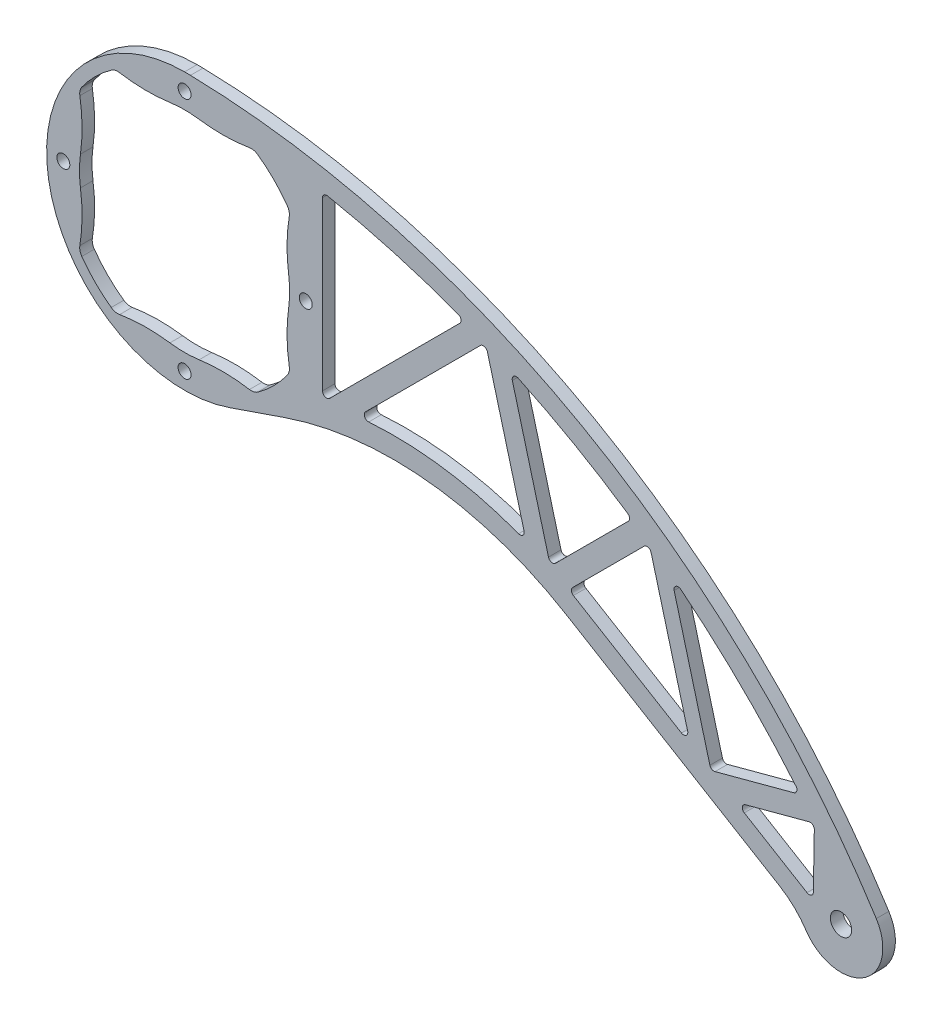
SolidWorks part; units mm, degrees
material "6061 合金"
ref_plane "前视基准面" through (0, 0, 0) normal (0, 0, 1) x (1, 0, 0)
ref_plane "上视基准面" through (0, 0, 0) normal (0, 1, 0) x (1, 0, 0)
ref_plane "右视基准面" through (0, 0, 0) normal (1, 0, 0) x (0, 0, -1)
other "Configuration Table"
sketch "草图2" plane through (0, 0, 0) normal (0, 0, 1) x (1, 0, 0)
  line L1 (10.7304, -31.2067) -> (23.987, -26.6485)
  line L2 (91.2325, -33.7454) -> (142.3676, -64.5004)
  line L3 (0, 0) -> (154.4016, 0) construction
  line L4 (0, 0) -> (157.0595, -65.0562) construction
  line L5 (0, 0) -> (0, -130.9869) construction
  arc A24 (0, 33) -> (10.7304, -31.2067) centre (0, 0) ccw
  arc A25 (148.7262, -70.5839) -> (165.4995, -59.6928) centre (157.0595, -65.0562) ccw
  arc A26 (1.4146, 32.9833) -> (165.4995, -59.6928) centre (-3.3007, -166.9611) cw
  circle A27 centre (-29, 0) radius 1.55
  arc A28 (23.987, -26.6485) -> (91.2325, -33.7454) centre (50, -102.3011) cw
  arc A29 (142.3676, -64.5004) -> (148.7262, -70.5839) centre (132.0595, -81.6393) cw
  arc A30 (1.4146, 32.9833) -> (0, 33) centre (0, -27) ccw
  arc A32 (-24.8547, -15.5614) -> (-24.7074, -3.4705) centre (-64.3186, -9.0345) ccw construction
  arc A33 (-24.8547, -15.5614) -> (-24.4235, -17.4211) centre (-22.3882, -15.9693) ccw construction
  arc A34 (-24.4235, -17.4211) -> (-17.4211, -24.4235) centre (0, 0) ccw construction
  arc A35 (-17.4211, -24.4235) -> (-15.5614, -24.8547) centre (-15.9693, -22.3882) ccw construction
  arc A36 (-3.4705, -24.7074) -> (-15.5614, -24.8547) centre (-9.0345, -64.3186) ccw construction
  arc A37 (-3.4705, -24.7074) -> (3.4705, -24.7074) centre (0, 0) ccw construction
  arc A38 (15.5614, -24.8547) -> (3.4705, -24.7074) centre (9.0345, -64.3186) ccw construction
  arc A39 (15.5614, -24.8547) -> (17.4211, -24.4235) centre (15.9693, -22.3882) ccw construction
  arc A40 (17.4211, -24.4235) -> (24.4235, -17.4211) centre (0, 0) ccw construction
  arc A41 (24.4235, -17.4211) -> (24.8547, -15.5614) centre (22.3882, -15.9693) ccw construction
  arc A42 (24.7074, -3.4705) -> (24.8547, -15.5614) centre (64.3186, -9.0345) ccw construction
  arc A43 (24.7074, -3.4705) -> (24.7074, 3.4705) centre (0, 0) ccw construction
  arc A44 (24.8547, 15.5614) -> (24.7074, 3.4705) centre (64.3186, 9.0345) ccw construction
  arc A45 (24.8547, 15.5614) -> (24.4235, 17.4211) centre (22.3882, 15.9693) ccw construction
  arc A46 (24.4235, 17.4211) -> (17.4211, 24.4235) centre (0, 0) ccw construction
  arc A47 (17.4211, 24.4235) -> (15.5614, 24.8547) centre (15.9693, 22.3882) ccw construction
  arc A48 (3.4705, 24.7074) -> (15.5614, 24.8547) centre (9.0345, 64.3186) ccw construction
  arc A49 (3.4705, 24.7074) -> (-3.4705, 24.7074) centre (0, 0) ccw construction
  arc A50 (-15.5614, 24.8547) -> (-3.4705, 24.7074) centre (-9.0345, 64.3186) ccw construction
  arc A51 (-15.5614, 24.8547) -> (-17.4211, 24.4235) centre (-15.9693, 22.3882) ccw construction
  arc A52 (-17.4211, 24.4235) -> (-24.4235, 17.4211) centre (0, 0) ccw construction
  arc A53 (-24.4235, 17.4211) -> (-24.8547, 15.5614) centre (-22.3882, 15.9693) ccw construction
  arc A54 (-24.7074, 3.4705) -> (-24.8547, 15.5614) centre (-64.3186, 9.0345) ccw construction
  arc A55 (-24.7074, 3.4705) -> (-24.7074, -3.4705) centre (0, 0) ccw construction
  arc A56 (-17.4792, 24.5049) -> (-24.5049, 17.4792) centre (0, 0) ccw
  arc A57 (-24.5049, 17.4792) -> (-24.9533, 15.5451) centre (-22.3882, 15.9693) ccw
  arc A58 (-24.8065, 3.4845) -> (-24.9533, 15.5451) centre (-64.3186, 9.0345) ccw
  arc A59 (-24.8065, 3.4845) -> (-24.8065, -3.4845) centre (0, 0) ccw
  arc A60 (-24.9533, -15.5451) -> (-24.8065, -3.4845) centre (-64.3186, -9.0345) ccw
  arc A61 (-24.9533, -15.5451) -> (-24.5049, -17.4792) centre (-22.3882, -15.9693) ccw
  arc A62 (-24.5049, -17.4792) -> (-17.4792, -24.5049) centre (0, 0) ccw
  arc A63 (-17.4792, -24.5049) -> (-15.5451, -24.9533) centre (-15.9693, -22.3882) ccw
  arc A64 (-3.4845, -24.8065) -> (-15.5451, -24.9533) centre (-9.0345, -64.3186) ccw
  arc A65 (-3.4845, -24.8065) -> (3.4845, -24.8065) centre (0, 0) ccw
  arc A66 (15.5451, -24.9533) -> (3.4845, -24.8065) centre (9.0345, -64.3186) ccw
  arc A67 (15.5451, -24.9533) -> (17.4792, -24.5049) centre (15.9693, -22.3882) ccw
  arc A68 (17.4792, -24.5049) -> (24.5049, -17.4792) centre (0, 0) ccw
  arc A69 (24.5049, -17.4792) -> (24.9533, -15.5451) centre (22.3882, -15.9693) ccw
  arc A70 (24.8065, -3.4845) -> (24.9533, -15.5451) centre (64.3186, -9.0345) ccw
  arc A71 (24.8065, -3.4845) -> (24.8065, 3.4845) centre (0, 0) ccw
  arc A72 (24.9533, 15.5451) -> (24.8065, 3.4845) centre (64.3186, 9.0345) ccw
  arc A73 (24.9533, 15.5451) -> (24.5049, 17.4792) centre (22.3882, 15.9693) ccw
  arc A74 (24.5049, 17.4792) -> (17.4792, 24.5049) centre (0, 0) ccw
  arc A75 (17.4792, 24.5049) -> (15.5451, 24.9533) centre (15.9693, 22.3882) ccw
  arc A76 (3.4845, 24.8065) -> (15.5451, 24.9533) centre (9.0345, 64.3186) ccw
  arc A77 (3.4845, 24.8065) -> (-3.4845, 24.8065) centre (0, 0) ccw
  arc A78 (-15.5451, 24.9533) -> (-3.4845, 24.8065) centre (-9.0345, 64.3186) ccw
  arc A79 (-15.5451, 24.9533) -> (-17.4792, 24.5049) centre (-15.9693, 22.3882) ccw
  circle A80 centre (0, 0) radius 29 construction
  circle A81 centre (0, 29) radius 1.55
  circle A82 centre (0, -29) radius 1.55
  arc A83 (15.5614, -24.8547) -> (3.4705, -24.7074) centre (9.0345, -64.3186) ccw construction
  circle A84 centre (29, 0) radius 1.55
  point P51 (147.0595, -65.0562)
  point P60 (29, 0)
  dimension "D3" = 3.1
  dimension "D5" = 66
  dimension "D6" = 20
  dimension "D7" = 80
  dimension "D9" = 20
  dimension "D10" = 200
  dimension "D11" = 60
  dimension "D13" = 50
  dimension "D1" = 170
  dimension "D2" = 130
  dimension "D4" = 29
  dimension "D8" = 22.5
  dimension "D12" = 0.1
  dimension "D14" = 25
extrude "凸台-拉伸1" add sketch "草图2" along normal blind 3
sketch "草图7" plane through (0, 0, 3) normal (0, 0, 1) x (1, 0, 0)
  circle A0 centre (157.0595, -65.0562) radius 2.55
  arc A1 (148.7262, -70.5839) -> (165.4995, -59.6928) centre (157.0595, -65.0562) ccw construction
  dimension "D1" = 5.1
extrude "切除-拉伸2" cut sketch "草图7" against normal blind 5
sketch "草图9" plane through (0, 0, 3) normal (0, 0, 1) x (1, 0, 0)
  line L0 (93.8095, -29.4607) -> (77.7146, -19.7805) construction
  line L2 (10.7304, -31.2067) -> (23.987, -26.6485)
  line L3 (91.2325, -33.7454) -> (142.3676, -64.5004)
  line L6 (33, 23.4192) -> (33, -16.6042)
  line L7 (34.7071, -17.3113) -> (65.8687, 13.8502)
  line L8 (70.7773, 11.6878) -> (43.2854, -15.8041)
  line L9 (72.4503, 11.2395) -> (81.2349, -21.5452)
  line L10 (78.4208, 8.276) -> (87.0701, -24.0039)
  line L11 (88.7431, -24.4522) -> (106.1707, -7.0247)
  line L12 (14.8183, -31.2257) -> (-22.149, -67.7394) construction
  line L13 (-23.9266, -76.5229) -> (-33.3984, -85.8785) construction
  line L14 (109.9456, -10.3208) -> (92.8385, -27.4279)
  line L15 (93.0302, -28.992) -> (118.8884, -44.5443)
  line L16 (93.8095, -29.4607) -> (144.9447, -60.2157) construction
  line L17 (91.2325, -33.7454) -> (142.3676, -64.5004) construction
  line L18 (111.6187, -10.7691) -> (120.3697, -43.4285)
  line L29 (117.1346, -15.8999) -> (125.6886, -47.8239)
  line L30 (93.8095, -29.4607) -> (144.9447, -60.2157)
  line L31 (93.8095, -29.4607) -> (144.9447, -60.2157) construction
  line L32 (126.9133, -48.531) -> (145.7798, -43.4758)
  line L33 (149.4125, -47.6788) -> (134.1757, -51.7615)
  line L34 (150.6712, -48.6626) -> (150.4368, -61.7685)
  line L35 (133.9191, -53.5844) -> (148.9215, -62.6075)
  arc A1 (79.917, -22.74) -> (44.0624, -17.5087) centre (50, -102.3011) ccw
  arc A7 (148.7262, -70.5839) -> (142.3676, -64.5004) centre (132.0595, -81.6393) ccw
  arc A8 (148.7262, -70.5839) -> (165.4995, -59.6928) centre (157.0595, -65.0562) ccw
  arc A9 (165.4995, -59.6928) -> (1.4146, 32.9833) centre (-3.3007, -166.9611) ccw
  arc A10 (1.4146, 32.9833) -> (0, 33) centre (0, -27) ccw
  arc A11 (117.1346, -15.8999) -> (118.7263, -14.861) centre (118.1005, -15.641) cw
  arc A12 (0, 33) -> (10.7304, -31.2067) centre (0, 0) ccw
  arc A13 (91.2325, -33.7454) -> (23.987, -26.6485) centre (50, -102.3011) ccw
  arc A15 (148.7262, -70.5839) -> (156.4086, -55.0774) centre (157.0595, -65.0562) ccw construction
  arc A21 (161.2795, -62.3745) -> (1.2967, 27.9847) centre (-3.3007, -166.9611) ccw construction
  arc A22 (93.8095, -29.4607) -> (-33.3984, -85.8785) centre (50, -102.3011) ccw construction
  arc A23 (65.5144, 15.493) -> (34.1923, 24.4006) centre (-3.3007, -166.9611) ccw
  arc A24 (106.0242, -5.4895) -> (79.8129, 9.4394) centre (-3.3007, -166.9611) ccw
  arc A27 (152.8929, -67.82) -> (144.9447, -60.2157) centre (132.0595, -81.6393) ccw construction
  arc A28 (165.4995, -59.6928) -> (1.4146, 32.9833) centre (-3.3007, -166.9611) ccw construction
  arc A29 (1.2967, 27.9847) -> (-23.9266, -76.5229) centre (0, -27) ccw construction
  arc A30 (1.4146, 32.9833) -> (15.1955, 31.0439) centre (0, -27) ccw construction
  circle A31 centre (3.5031, 49.1035) radius 21.5142 construction
  arc A32 (-23.9266, -76.5229) -> (-23.9266, -76.5229) centre (-23.9266, -76.5229) ccw construction
  arc A33 (-23.9266, -76.5229) -> (-23.9266, -76.5229) centre (-23.9266, -76.5229) cw construction
  arc A34 (15.1955, 31.0439) -> (14.8183, -31.2257) centre (0, 0) ccw construction
  arc A35 (91.2325, -33.7454) -> (-22.149, -67.7394) centre (50, -102.3011) ccw construction
  arc A36 (148.7262, -70.5839) -> (142.3676, -64.5004) centre (132.0595, -81.6393) ccw construction
  arc A37 (148.7262, -70.5839) -> (165.4995, -59.6928) centre (157.0595, -65.0562) ccw construction
  arc A38 (152.8929, -67.82) -> (161.2795, -62.3745) centre (157.0595, -65.0562) ccw construction
  arc A42 (92.8385, -27.4279) -> (93.0302, -28.992) centre (93.5456, -28.135) ccw
  arc A43 (109.9456, -10.3208) -> (111.6187, -10.7691) centre (110.6527, -11.0279) cw
  arc A44 (106.1707, -7.0247) -> (106.0242, -5.4895) centre (105.4636, -6.3176) ccw
  arc A45 (78.4208, 8.276) -> (79.8129, 9.4394) centre (79.3867, 8.5348) cw
  arc A46 (87.0701, -24.0039) -> (88.7431, -24.4522) centre (88.036, -23.7451) ccw
  arc A47 (43.2854, -15.8041) -> (44.0624, -17.5087) centre (43.9926, -16.5112) ccw
  arc A48 (70.7773, 11.6878) -> (72.4503, 11.2395) centre (71.4844, 10.9806) cw
  arc A49 (65.8687, 13.8502) -> (65.5144, 15.493) centre (65.1615, 14.5573) ccw
  arc A50 (33, -16.6042) -> (34.7071, -17.3113) centre (34, -16.6042) ccw
  arc A51 (33, 23.4192) -> (34.1923, 24.4006) centre (34, 23.4192) cw
  arc A52 (81.2349, -21.5452) -> (79.917, -22.74) centre (80.269, -21.804) cw
  arc A53 (120.3697, -43.4285) -> (118.8884, -44.5443) centre (119.4038, -43.6873) cw
  arc A58 (145.7798, -43.4758) -> (146.2881, -41.8684) centre (145.521, -42.5099) ccw
  arc A60 (125.6886, -47.8239) -> (126.9133, -48.531) centre (126.6545, -47.5651) ccw
  arc A61 (134.1757, -51.7615) -> (133.9191, -53.5844) centre (134.4345, -52.7274) ccw
  arc A62 (149.4125, -47.6788) -> (150.6712, -48.6626) centre (149.6713, -48.6447) cw
  arc A63 (161.2795, -62.3745) -> (1.2967, 27.9847) centre (-3.3007, -166.9611) ccw
  arc A64 (161.2795, -62.3745) -> (156.4086, -55.0774) centre (-3.3007, -166.9611) ccw construction
  arc A65 (146.2881, -41.8684) -> (118.7263, -14.861) centre (-3.3007, -166.9611) ccw
  arc A66 (152.8929, -67.82) -> (144.9447, -60.2157) centre (132.0595, -81.6393) ccw
  arc A67 (152.8929, -67.82) -> (144.9447, -60.2157) centre (132.0595, -81.6393) ccw construction
  arc A68 (150.4368, -61.7685) -> (148.9215, -62.6075) centre (149.4369, -61.7506) cw
  circle A69 centre (29, 0) radius 1.55 construction
  point P54 (119.853, -45.1244)
  point P60 (91.9338, -28.3326)
  point P63 (111.1704, -9.096)
  point P66 (107.0242, -6.1711)
  point P71 (87.5184, -25.6769)
  point P76 (72.002, 12.9125)
  point P79 (66.9597, 14.9413)
  point P82 (33, -19.0185)
  point P88 (147.2865, -43.0721)
  point P96 (125.9474, -48.7899)
  point P99 (131.9014, -52.3709)
  point P103 (150.6949, -47.3352)
  point P106 (150.4058, -63.5002)
  dimension "D12" = 5
  dimension "D14" = 90
  dimension "D15" = 1
  dimension "D16" = 1
  dimension "D17" = 5
  dimension "D18" = 5
  dimension "D13" = 4
  dimension "D19" = 1
  dimension "D3" = 4
  dimension "D4" = 45
  dimension "D5" = 5
  dimension "D6" = 60
  dimension "D7" = 5
  dimension "D8" = 60
  dimension "D9" = 5
  dimension "D10" = 60
  dimension "D11" = 5
  dimension "D20" = 60
  dimension "D1" = 0
  dimension "D2" = 5
extrude "切除-拉伸4" cut sketch "草图9" against normal through all
sketch "草图10" plane through (0, 0, 3) normal (0, 0, 1) x (1, 0, 0)
  arc A48 (-3.4984, -24.9055) -> (-15.5288, -25.052) centre (-9.0345, -64.3186) ccw
  arc A49 (-17.5372, -24.5863) -> (-15.5288, -25.052) centre (-15.9693, -22.3882) ccw
  arc A50 (-24.5863, -17.5372) -> (-17.5372, -24.5863) centre (0, 0) ccw
  arc A51 (-25.052, -15.5288) -> (-24.5863, -17.5372) centre (-22.3882, -15.9693) ccw
  arc A52 (-25.052, -15.5288) -> (-24.9055, -3.4984) centre (-64.3186, -9.0345) ccw
  arc A53 (-24.9055, 3.4984) -> (-24.9055, -3.4984) centre (0, 0) ccw
  arc A54 (-24.9055, 3.4984) -> (-25.052, 15.5288) centre (-64.3186, 9.0345) ccw
  arc A55 (-24.5863, 17.5372) -> (-25.052, 15.5288) centre (-22.3882, 15.9693) ccw
  arc A56 (-17.5372, 24.5863) -> (-24.5863, 17.5372) centre (0, 0) ccw
  arc A57 (-15.5288, 25.052) -> (-17.5372, 24.5863) centre (-15.9693, 22.3882) ccw
  arc A58 (-15.5288, 25.052) -> (-3.4984, 24.9055) centre (-9.0345, 64.3186) ccw
  arc A59 (3.4984, 24.9055) -> (-3.4984, 24.9055) centre (0, 0) ccw
  arc A60 (3.4984, 24.9055) -> (15.5288, 25.052) centre (9.0345, 64.3186) ccw
  arc A61 (17.5372, 24.5863) -> (15.5288, 25.052) centre (15.9693, 22.3882) ccw
  arc A62 (24.5863, 17.5372) -> (17.5372, 24.5863) centre (0, 0) ccw
  arc A63 (25.052, 15.5288) -> (24.5863, 17.5372) centre (22.3882, 15.9693) ccw
  arc A64 (25.052, 15.5288) -> (24.9055, 3.4984) centre (64.3186, 9.0345) ccw
  arc A65 (24.9055, -3.4984) -> (24.9055, 3.4984) centre (0, 0) ccw
  arc A66 (24.9055, -3.4984) -> (25.052, -15.5288) centre (64.3186, -9.0345) ccw
  arc A67 (24.5863, -17.5372) -> (25.052, -15.5288) centre (22.3882, -15.9693) ccw
  arc A68 (17.5372, -24.5863) -> (24.5863, -17.5372) centre (0, 0) ccw
  arc A69 (15.5288, -25.052) -> (17.5372, -24.5863) centre (15.9693, -22.3882) ccw
  arc A70 (15.5288, -25.052) -> (3.4984, -24.9055) centre (9.0345, -64.3186) ccw
  arc A71 (-3.4984, -24.9055) -> (3.4984, -24.9055) centre (0, 0) ccw
  arc A72 (-3.4984, -24.9055) -> (-15.5288, -25.052) centre (-9.0345, -64.3186) ccw
  arc A73 (-17.5372, -24.5863) -> (-15.5288, -25.052) centre (-15.9693, -22.3882) ccw
  arc A74 (-24.5863, -17.5372) -> (-17.5372, -24.5863) centre (0, 0) ccw
  arc A75 (-25.052, -15.5288) -> (-24.5863, -17.5372) centre (-22.3882, -15.9693) ccw
  arc A76 (-25.052, -15.5288) -> (-24.9055, -3.4984) centre (-64.3186, -9.0345) ccw
  arc A77 (-24.9055, 3.4984) -> (-24.9055, -3.4984) centre (0, 0) ccw
  arc A78 (-24.9055, 3.4984) -> (-25.052, 15.5288) centre (-64.3186, 9.0345) ccw
  arc A79 (-24.5863, 17.5372) -> (-25.052, 15.5288) centre (-22.3882, 15.9693) ccw
  arc A80 (-17.5372, 24.5863) -> (-24.5863, 17.5372) centre (0, 0) ccw
  arc A81 (-15.5288, 25.052) -> (-17.5372, 24.5863) centre (-15.9693, 22.3882) ccw
  arc A82 (-15.5288, 25.052) -> (-3.4984, 24.9055) centre (-9.0345, 64.3186) ccw
  arc A83 (3.4984, 24.9055) -> (-3.4984, 24.9055) centre (0, 0) ccw
  arc A84 (3.4984, 24.9055) -> (15.5288, 25.052) centre (9.0345, 64.3186) ccw
  arc A85 (17.5372, 24.5863) -> (15.5288, 25.052) centre (15.9693, 22.3882) ccw
  arc A86 (24.5863, 17.5372) -> (17.5372, 24.5863) centre (0, 0) ccw
  arc A87 (25.052, 15.5288) -> (24.5863, 17.5372) centre (22.3882, 15.9693) ccw
  arc A88 (25.052, 15.5288) -> (24.9055, 3.4984) centre (64.3186, 9.0345) ccw
  arc A89 (24.9055, -3.4984) -> (24.9055, 3.4984) centre (0, 0) ccw
  arc A90 (24.9055, -3.4984) -> (25.052, -15.5288) centre (64.3186, -9.0345) ccw
  arc A91 (24.5863, -17.5372) -> (25.052, -15.5288) centre (22.3882, -15.9693) ccw
  arc A92 (17.5372, -24.5863) -> (24.5863, -17.5372) centre (0, 0) ccw
  arc A93 (15.5288, -25.052) -> (17.5372, -24.5863) centre (15.9693, -22.3882) ccw
  arc A94 (15.5288, -25.052) -> (3.4984, -24.9055) centre (9.0345, -64.3186) ccw
  arc A95 (-3.4984, -24.9055) -> (3.4984, -24.9055) centre (0, 0) ccw
  dimension "D1" = 0.1
extrude "切除-拉伸5" cut sketch "草图10" against normal through all
